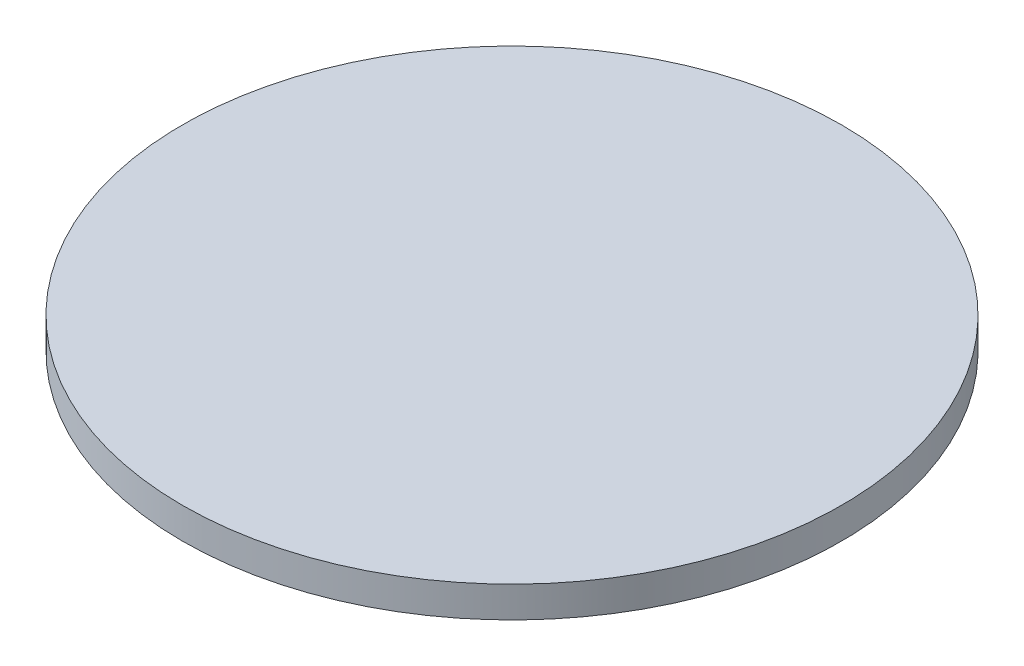
SolidWorks part; units mm, degrees
ref_plane "Спереди" through (0, 0, 0) normal (0, 0, 1) x (1, 0, 0)
ref_plane "Сверху" through (0, 0, 0) normal (0, 1, 0) x (1, 0, 0)
ref_plane "Справа" through (0, 0, 0) normal (1, 0, 0) x (0, 0, -1)
sketch "Эскиз1" plane through (0, 0, 0) normal (0, 1, 0) x (1, 0, 0)
  circle A0 centre (0, 0) radius 42.5
extrude "Вытянуть1" add sketch "Эскиз1" along normal blind 4
